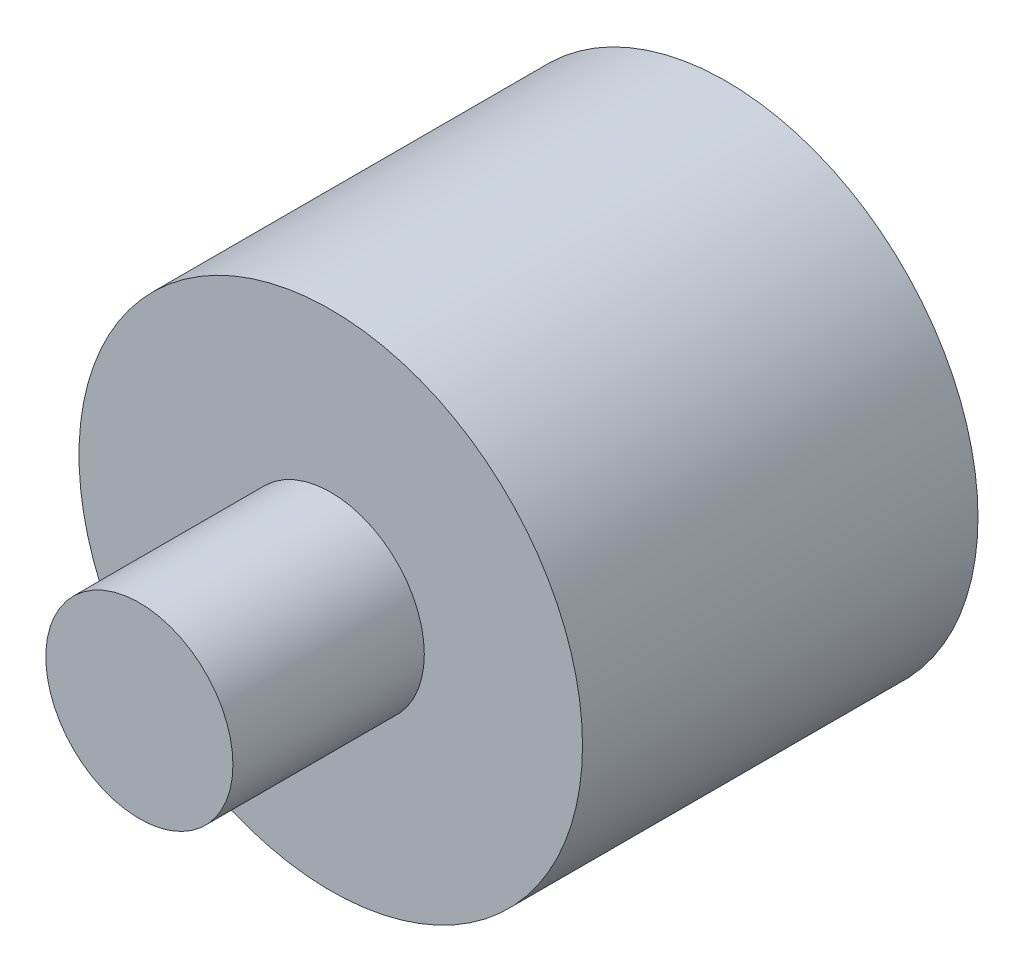
SolidWorks part; units mm, degrees
ref_plane "Front Plane" through (0, 0, 0) normal (0, 0, 1) x (1, 0, 0)
ref_plane "Top Plane" through (0, 0, 0) normal (0, 1, 0) x (1, 0, 0)
ref_plane "Right Plane" through (0, 0, 0) normal (1, 0, 0) x (0, 0, -1)
sketch "Sketch1" plane through (0, 0, 0) normal (0, 0, 1) x (1, 0, 0)
  circle A0 centre (0, 0) radius 150.368
  dimension "D1" = 300.736
extrude "Boss-Extrude1" add sketch "Sketch1" along normal blind 236.22
sketch "Sketch2" plane through (0, 0, 236.22) normal (0, 0, 1) x (1, 0, 0)
  circle A0 centre (0, 0) radius 55.88
  dimension "D1" = 111.76
extrude "Boss-Extrude2" add sketch "Sketch2" along normal blind 114.3
